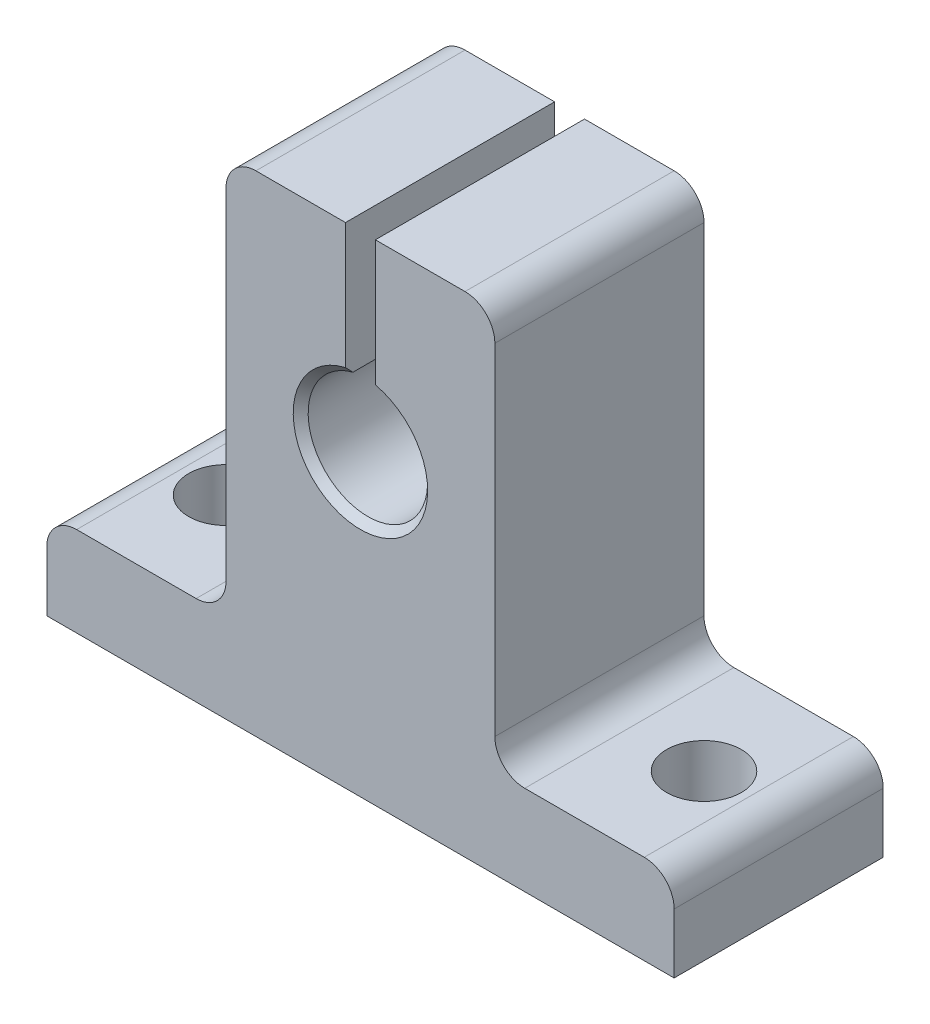
SolidWorks part; units mm, degrees
material "6061-T6 (SS)"
ref_plane "Front Plane" through (0, 0, 0) normal (0, 0, 1) x (1, 0, 0)
ref_plane "Top Plane" through (0, 0, 0) normal (0, 1, 0) x (1, 0, 0)
ref_plane "Right Plane" through (0, 0, 0) normal (1, 0, 0) x (0, 0, -1)
sketch "Sketch1" plane through (0, 0, 0) normal (0, 0, 1) x (1, 0, 0)
  line L0 (-21, 4) -> (-21, 0)
  line L1 (-21, 0) -> (21, 0)
  line L2 (21, 0) -> (21, 4)
  line L3 (19, 6) -> (11, 6)
  line L4 (9, 8) -> (9, 30.8)
  line L5 (7, 32.8) -> (1, 32.8)
  line L6 (1, 32.8) -> (1, 23.873)
  line L8 (-1, 23.873) -> (-1, 32.8)
  line L9 (-1, 32.8) -> (-7, 32.8)
  line L10 (-9, 30.8) -> (-9, 8)
  line L11 (-11, 6) -> (-19, 6)
  line L12 (-9, 32.8) -> (9, 32.8) construction
  arc A0 (-1, 23.873) -> (1, 23.873) centre (0, 20) ccw
  arc A1 (9, 30.8) -> (7, 32.8) centre (7, 30.8) ccw
  arc A2 (-7, 32.8) -> (-9, 30.8) centre (-7, 30.8) ccw
  arc A3 (-9, 8) -> (-11, 6) centre (-11, 8) cw
  arc A4 (11, 6) -> (9, 8) centre (11, 8) cw
  arc A5 (21, 4) -> (19, 6) centre (19, 4) ccw
  arc A6 (-21, 4) -> (-19, 6) centre (-19, 4) cw
  point P9 (0, 32.8)
  point P14 (0, 0)
  point P28 (21, 6)
  dimension "D5" = 8
  dimension "D9" = 2
  dimension "D1" = 42
  dimension "D2" = 32.8
  dimension "D3" = 6
  dimension "D4" = 20
  dimension "D6" = 2
  dimension "D7" = 1
  dimension "D8" = 18
extrude "Boss-Extrude1" add sketch "Sketch1" along normal blind 14
chamfer "Chamfer1" distance 0.5 angle 45 2 edges at (0, 16, 0) (0, 16, 14)
sketch "Sketch2" plane through (0, 6, 0) normal (0, 1, 0) x (1, 0, 0)
  line L1 (-16, -7) -> (16, -7) construction
  line L2 (-21, -14) -> (-21, 0) construction
  point P0 (-16, -7)
  point P1 (16, -7)
  point P2 (0, -7)
  point P10 (-21, -7)
  dimension "D1" = 32
hole_wizard "M6x1.0 Tapped Hole1" positions "Sketch3" profile "Sketch5" tap size "M6x1.0" standard "ANSI Metric" end condition through all
sketch "Sketch3" plane through (0, 6, 0) normal (0, 1, 0) x (1, 0, 0)
  point P0 (-16, -7)
  point P3 (16, -7)
sketch "Sketch5" plane through (-16, 6, 7) normal (1, 0, 0) x (0, 0, 1)
  line L0 (0, 0) -> (0, 6)
  line L1 (0, 6) -> (2.5, 6)
  line L2 (2.5, 6) -> (2.5, 0)
  line L5 (2.5, 0) -> (0, 0)
  line L11 (0, -6.35) -> (0, 107.95) construction
  dimension "Thru Tap Drill Dia." = 5
  dimension "Thru Tap Drill Depth" = 6
cosmetic thread "Hole Thread1" parameters "D2"=6
cosmetic thread "Hole Thread2" parameters "D2"=6
ref_plane "Plane1" through (0, 0, 7) normal (0, 0, -1) x (-1, 0, 0)
